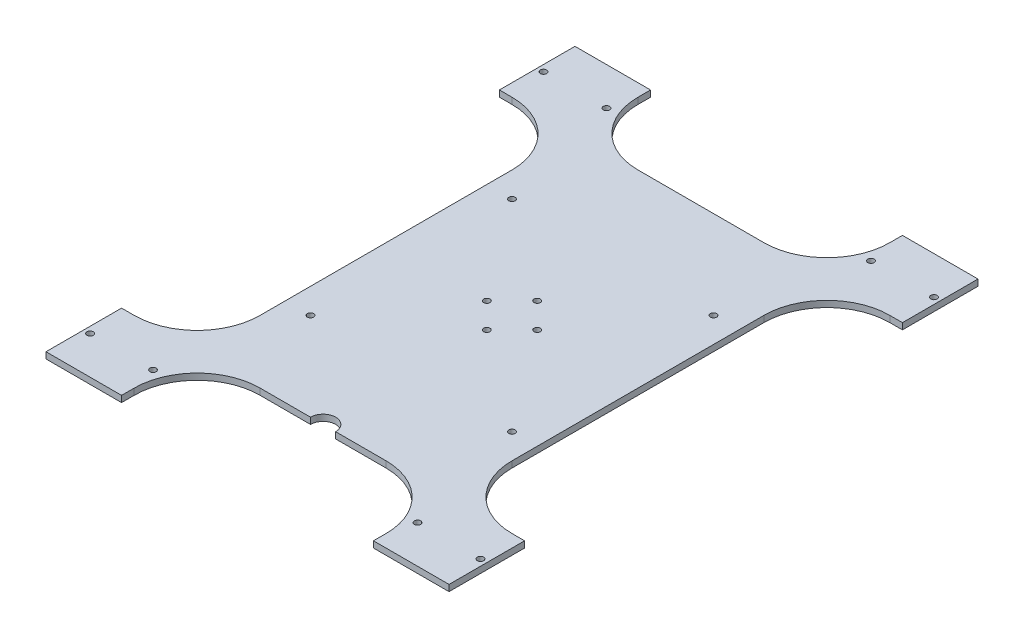
SolidWorks part; units mm, degrees
ref_plane "Front Plane" through (0, 0, 0) normal (0, 0, 1) x (1, 0, 0)
ref_plane "Top Plane" through (0, 0, 0) normal (0, 1, 0) x (1, 0, 0)
ref_plane "Right Plane" through (0, 0, 0) normal (1, 0, 0) x (0, 0, -1)
sketch "Sketch1" plane through (0, 0, 0) normal (0, 1, 0) x (1, 0, 0)
  line L0 (0, 150) -> (200, 150) construction
  line L1 (50, 0) -> (150, 0)
  line L2 (0, 50) -> (0, 250)
  line L3 (50, 300) -> (150, 300)
  line L4 (200, 50) -> (200, 250)
  line L5 (-50, 300) -> (-60, 300)
  line L6 (0, 350) -> (0, 360)
  line L7 (0, 360) -> (-60, 360)
  line L8 (-60, 300) -> (-60, 360)
  line L9 (250, 300) -> (260, 300)
  line L10 (200, 350) -> (200, 360)
  line L11 (200, 360) -> (260, 360)
  line L12 (260, 300) -> (260, 360)
  line L13 (250, 0) -> (260, 0)
  line L14 (200, -50) -> (200, -60)
  line L15 (200, -60) -> (260, -60)
  line L16 (260, 0) -> (260, -60)
  line L17 (-50, 0) -> (-60, 0)
  line L18 (0, -50) -> (0, -60)
  line L19 (0, -60) -> (-60, -60)
  line L20 (-60, 0) -> (-60, -60)
  line L21 (100, 300) -> (100, 0) construction
  circle A0 centre (20, 230) radius 2.5
  circle A1 centre (20, 70) radius 2.5
  circle A2 centre (180, 70) radius 2.5
  circle A3 centre (180, 230) radius 2.5
  arc A4 (0, 50) -> (-50, 0) centre (-50, 50) cw
  arc A5 (0, -50) -> (50, 0) centre (50, -50) cw
  arc A6 (150, 0) -> (200, -50) centre (150, -50) cw
  arc A7 (250, 0) -> (200, 50) centre (250, 50) cw
  arc A8 (250, 300) -> (200, 250) centre (250, 250) ccw
  arc A9 (150, 300) -> (200, 350) centre (150, 350) ccw
  arc A10 (50, 300) -> (0, 350) centre (50, 350) cw
  arc A11 (0, 250) -> (-50, 300) centre (-50, 250) ccw
  circle A12 centre (-55, -30) radius 2.5
  circle A13 centre (-5, -30) radius 2.5
  circle A14 centre (-55, 330) radius 2.5
  circle A15 centre (-5, 330) radius 2.5
  circle A16 centre (205, 330) radius 2.5
  circle A17 centre (255, 330) radius 2.5
  circle A18 centre (205, -30) radius 2.5
  circle A19 centre (255, -30) radius 2.5
  circle A24 centre (100, 170) radius 2.5
  circle A25 centre (120, 150) radius 2.5
  circle A26 centre (80, 150) radius 2.5
  circle A27 centre (100, 130) radius 2.5
  point P5 (20, 230)
  point P6 (60, 280)
  point P7 (40, 280)
  point P8 (80, 280)
  point P9 (100, 280)
  point P10 (140, 280)
  point P11 (160, 280)
  point P12 (180, 230)
  point P13 (120, 280)
  point P14 (20, 70)
  point P15 (180, 70)
  point P41 (0, 0)
  point P47 (200, 0)
  point P53 (200, 300)
  point P59 (0, 300)
  point P60 (-55, -30)
  point P61 (-5, -30)
  point P66 (205, -30)
  point P67 (255, -30)
  point P68 (255, 330)
  point P69 (205, 330)
  point P70 (-5, 330)
  point P71 (-55, 330)
  point P101 (120, 150)
  point P102 (100, 170)
  point P103 (80, 150)
  point P104 (100, 130)
  dimension "D18" = 60
  dimension "D27" = 50
  dimension "D30" = 30
  dimension "D44" = 80
  dimension "D53" = 20
  dimension "D1" = 200
  dimension "D2" = 300
  dimension "D6" = 20
  dimension "D7" = 20
  dimension "D8" = 20
  dimension "D9" = 20
  dimension "D10" = 20
  dimension "D11" = 20
  dimension "D12" = 80
  dimension "D13" = 80
  dimension "D14" = 80
  dimension "D15" = 80
  dimension "D16" = 80
  dimension "D19" = 60
  dimension "D20" = 60
  dimension "D21" = 60
  dimension "D22" = 320
  dimension "D23" = 60
  dimension "D24" = 60
  dimension "D25" = 60
  dimension "D26" = 60
  dimension "D28" = 5
  dimension "D29" = 5
  dimension "D31" = 30
  dimension "D32" = 5
  dimension "D33" = 30
  dimension "D34" = 5
  dimension "D35" = 30
  dimension "D36" = 5
  dimension "D37" = 5
  dimension "D38" = 30
  dimension "D39" = 30
  dimension "D40" = 5
  dimension "D41" = 5
  dimension "D42" = 30
  dimension "D43" = 30
  dimension "D54" = 20
  dimension "D55" = 20
  dimension "D56" = 20
extrude "Boss-Extrude1" add sketch "Sketch1" along normal blind 5
sketch "Sketch3" plane through (0, 5, 0) normal (0, 1, 0) x (1, 0, 0)
  line L0 (50, 0) -> (150, 0) construction
  line L1 (100, 0) -> (100, 98.5521) construction
  arc A0 (110, 0) -> (90, 0) centre (100, 0) ccw
  point P0 (110, 0)
  point P1 (90, 0)
  point P4 (100, 0)
  dimension "D1" = 10
  dimension "D2" = 10
extrude "Cut-Extrude2" cut sketch "Sketch3" against normal through all and the other way through all
